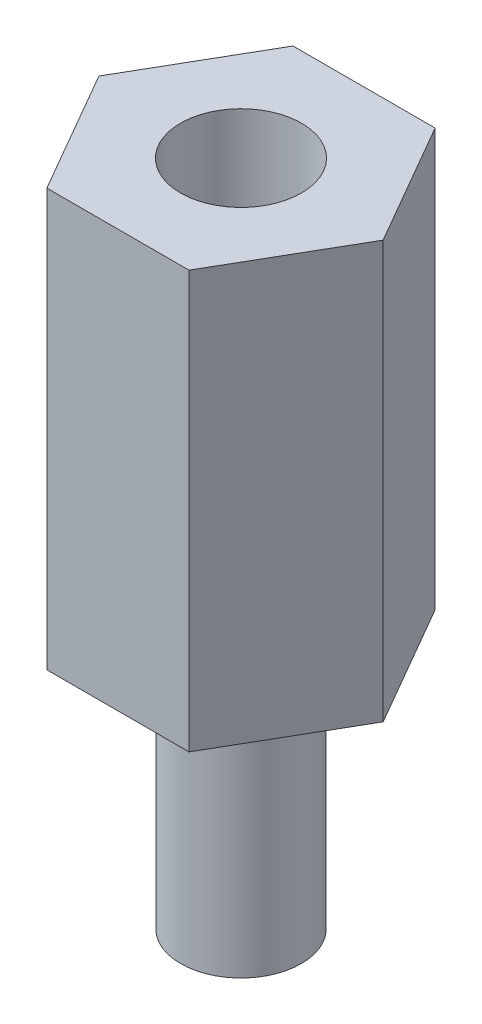
SolidWorks part; units mm, degrees
ref_plane "Front Plane" through (0, 0, 0) normal (0, 0, 1) x (1, 0, 0)
ref_plane "Top Plane" through (0, 0, 0) normal (0, 1, 0) x (1, 0, 0)
ref_plane "Right Plane" through (0, 0, 0) normal (1, 0, 0) x (0, 0, -1)
sketch "Sketch1" plane through (0, 0, 0) normal (0, 1, 0) x (1, 0, 0)
  line L1 (3.4064, 0) -> (1.7032, 2.95)
  line L2 (1.7032, 2.95) -> (-1.7032, 2.95)
  line L3 (-1.7032, 2.95) -> (-3.4064, 0)
  line L4 (-3.4064, 0) -> (-1.7032, -2.95)
  line L5 (-1.7032, -2.95) -> (1.7032, -2.95)
  line L6 (1.7032, -2.95) -> (3.4064, 0)
  circle A0 centre (0, 0) radius 2.95 construction
  dimension "D1" = 5.9
extrude "Boss-Extrude1" add sketch "Sketch1" along normal blind 10
sketch "Sketch2" plane through (0, 0, 0) normal (0, -1, 0) x (1, 0, 0)
  circle A0 centre (0, 0) radius 1.445
  dimension "D1" = 2.89
extrude "Boss-Extrude2" add sketch "Sketch2" along normal blind 6
sketch "Sketch4" plane through (0, 10, 0) normal (0, 1, 0) x (1, 0, 0)
  circle A0 centre (0, 0) radius 1.45
  dimension "D1" = 2.9
extrude "Cut-Extrude1" cut sketch "Sketch4" against normal blind 6
